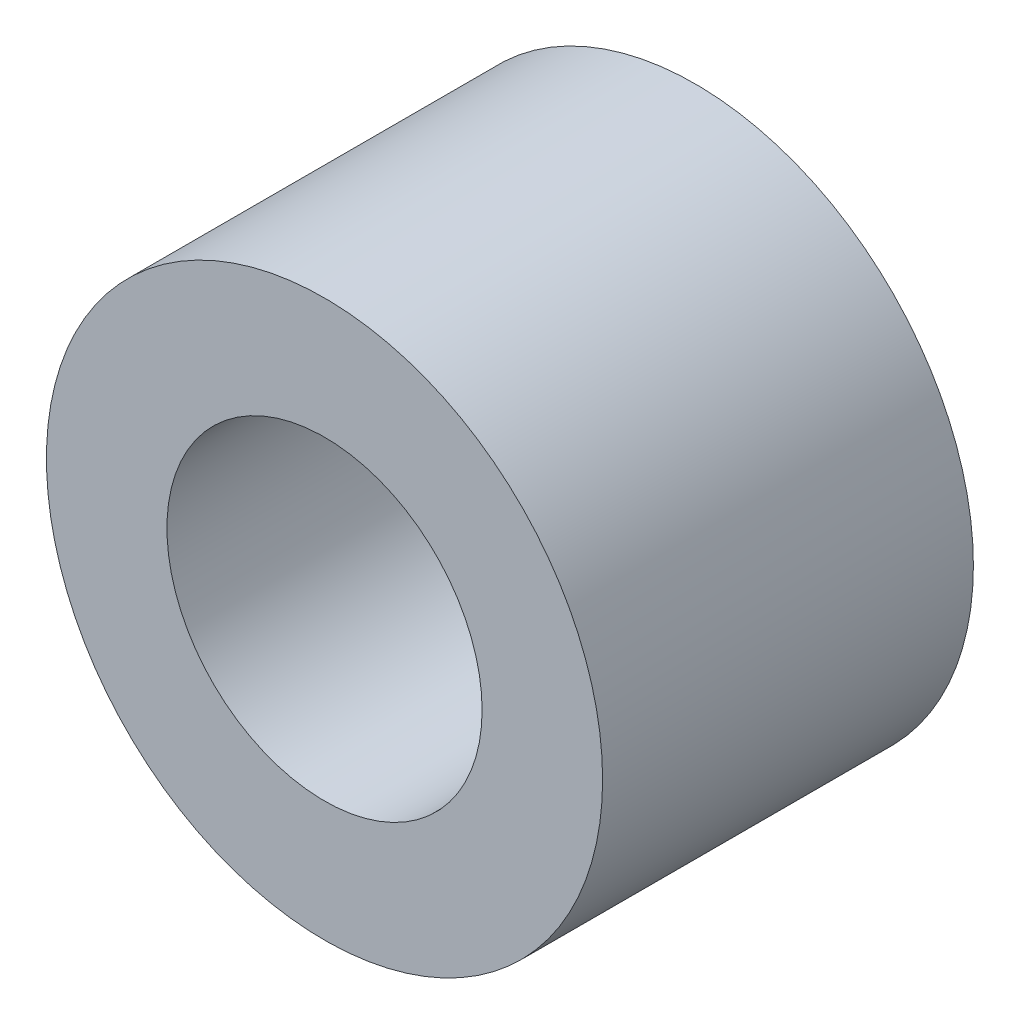
SolidWorks part; units mm, degrees
material "6061-T6 (SS)"
ref_plane "Front Plane" through (0, 0, 0) normal (0, 0, 1) x (1, 0, 0)
ref_plane "Top Plane" through (0, 0, 0) normal (0, 1, 0) x (1, 0, 0)
ref_plane "Right Plane" through (0, 0, 0) normal (1, 0, 0) x (0, 0, -1)
sketch "Sketch1" plane through (0, 0, 0) normal (0, 0, 1) x (1, 0, 0)
  circle A0 centre (0, 0) radius 3
  circle A1 centre (0, 0) radius 1.7
extrude "Base_Spacer" add sketch "Sketch1" along normal blind 4
